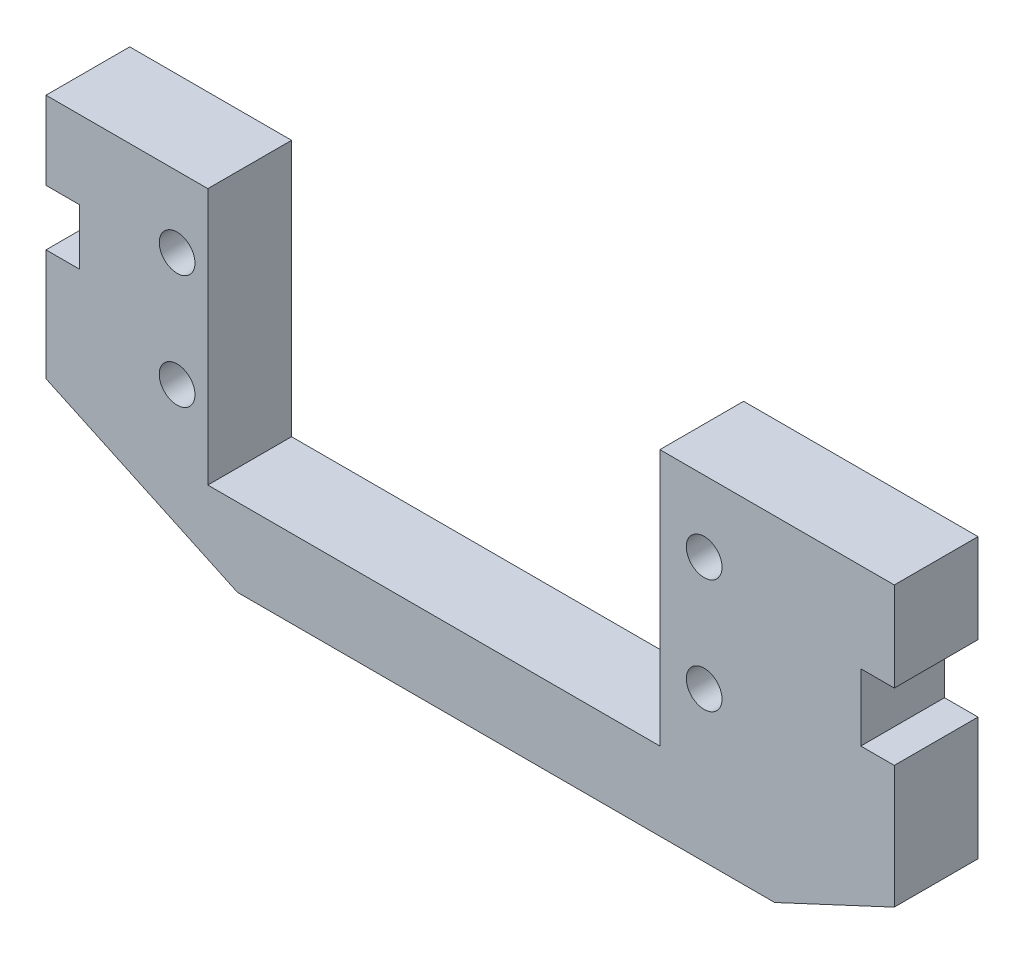
SolidWorks part; units mm, degrees
material "Plywood"
ref_plane "Plan de face" through (0, 0, 0) normal (0, 0, 1) x (1, 0, 0)
ref_plane "Plan de dessus" through (0, 0, 0) normal (0, 1, 0) x (1, 0, 0)
ref_plane "Plan de droite" through (0, 0, 0) normal (1, 0, 0) x (0, 0, -1)
sketch "Esquisse1" plane through (0, 0, 0) normal (0, 0, 1) x (1, 0, 0)
  line L0 (0, 0) -> (0, -30)
  line L1 (0, -30) -> (76, -30)
  line L2 (76, -30) -> (76, 0)
  line L3 (76, 0) -> (55, 0)
  line L4 (55, 0) -> (55, -23)
  line L5 (55, -23) -> (14.5, -23)
  line L6 (14.5, -23) -> (14.5, 0)
  line L7 (14.5, 0) -> (0, 0)
  dimension "D1" = 40.5
  dimension "D2" = 14.5
  dimension "D3" = 30
  dimension "D4" = 76
  dimension "D5" = 23
extrude "Boss.-Extru.1" add sketch "Esquisse1" along normal blind 7.5
sketch "Esquisse2" plane through (0, 0, 0) normal (0, 0, -1) x (-1, 0, 0)
  circle A0 centre (-11.7466, -16.5763) radius 1.6
  circle A1 centre (-11.7466, -6.3488) radius 1.6
  circle A2 centre (-58.9661, -16.5763) radius 1.6
  circle A3 centre (-58.9661, -6.3488) radius 1.6
  dimension "D1" = 3.2
  dimension "D2" = 3.2
  dimension "D3" = 3.2
  dimension "D4" = 3.2
extrude "Enlèv. mat.-Extru.1" cut sketch "Esquisse2" against normal through all
chamfer "Chanfrein1" distance 8 angle 65 1 edges at (0, -30, 3.75)
chamfer "Chanfrein2" distance 5 angle 65 1 edges at (76, -30, 3.75)
sketch "Esquisse3" plane through (0, 0, 7.5) normal (0, 0, 1) x (1, 0, 0)
  line L0 (76, -25) -> (76, 0) construction
  line L1 (76, -8) -> (73, -8)
  line L2 (76, -8) -> (76, -14)
  line L3 (76, -14) -> (73, -14)
  line L4 (73, -8) -> (73, -14)
  line L5 (76, 0) -> (55, 0) construction
  line L6 (0, 0) -> (0, -22) construction
  line L7 (0, -7) -> (3, -7)
  line L8 (0, -7) -> (0, -12)
  line L9 (0, -12) -> (3, -12)
  line L10 (3, -7) -> (3, -12)
  line L11 (14.5, 0) -> (0, 0) construction
  dimension "D1" = 8
  dimension "D2" = 6
  dimension "D3" = 3
  dimension "D4" = 3
  dimension "D5" = 7
  dimension "D6" = 5
extrude "Enlèv. mat.-Extru.2" cut sketch "Esquisse3" against normal through all
